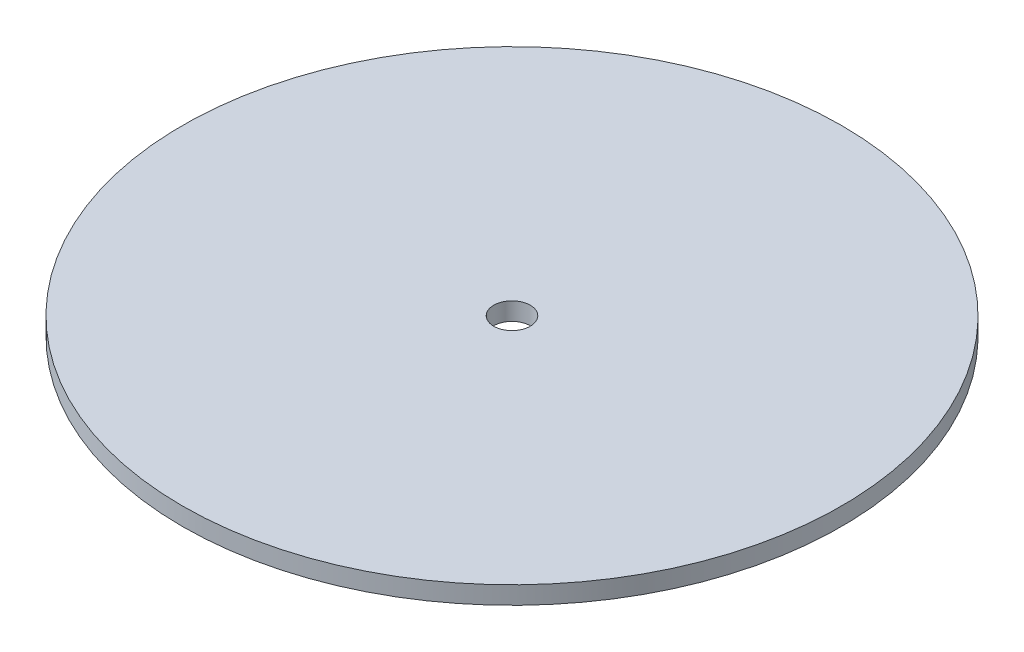
SolidWorks part; units mm, degrees
ref_plane "Front Plane" through (0, 0, 0) normal (0, 0, 1) x (1, 0, 0)
ref_plane "Top Plane" through (0, 0, 0) normal (0, 1, 0) x (1, 0, 0)
ref_plane "Right Plane" through (0, 0, 0) normal (1, 0, 0) x (0, 0, -1)
sketch "Sketch1" plane through (0, 0, 0) normal (0, 1, 0) x (1, 0, 0)
  circle A0 centre (0, 0) radius 74.04
  circle A1 centre (0, 0) radius 4.1
  dimension "D1" = 148.08
  dimension "D2" = 8.2
extrude "Boss-Extrude1" add sketch "Sketch1" along normal blind 4
